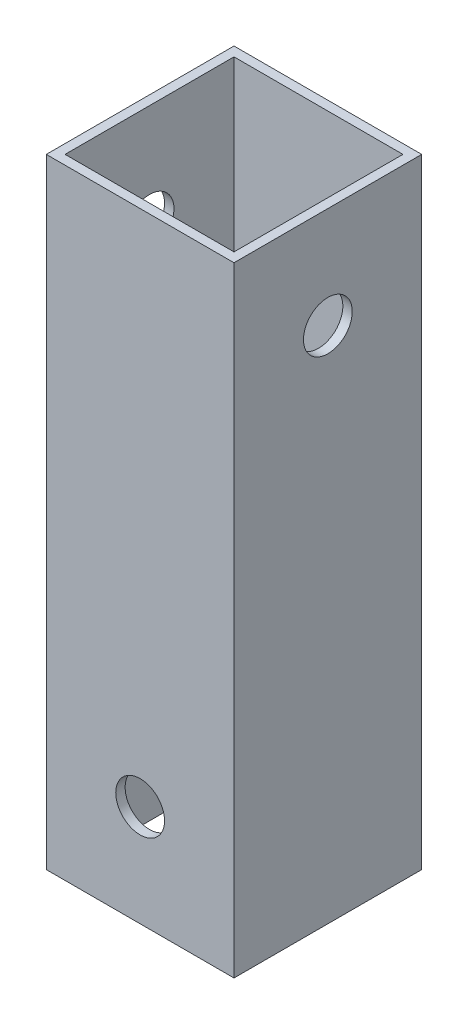
SolidWorks part; units mm, degrees
ref_plane "Front Plane" through (0, 0, 0) normal (0, 0, 1) x (1, 0, 0)
ref_plane "Top Plane" through (0, 0, 0) normal (0, 1, 0) x (1, 0, 0)
ref_plane "Right Plane" through (0, 0, 0) normal (1, 0, 0) x (0, 0, -1)
sketch "Sketch1" plane through (0, 0, 0) normal (0, 1, 0) x (1, 0, 0)
  line L9 (0, 0) -> (20, 0)
  line L10 (0, 0) -> (0, 20)
  line L11 (0, 20) -> (20, 20)
  line L12 (20, 0) -> (20, 20)
  line L13 (1, 1) -> (19, 1)
  line L14 (1, 1) -> (1, 19)
  line L15 (1, 19) -> (19, 19)
  line L16 (19, 1) -> (19, 19)
  dimension "D1" = 20
  dimension "D2" = 20
  dimension "D3" = 18
  dimension "D4" = 1
  dimension "D5" = 1
  dimension "D6" = 18
extrude "Boss-Extrude1" add sketch "Sketch1" along normal blind 66
sketch "Sketch2" plane through (20, 0, 0) normal (1, 0, 0) x (0, 0, -1)
  line L0 (0, 66) -> (20, 66) construction
  line L1 (20, 66) -> (20, 0) construction
  circle A0 centre (10, 55.2) radius 2.6
  dimension "D1" = 5.2
  dimension "D2" = 10.8
  dimension "D3" = 10
extrude "Cut-Extrude1" cut sketch "Sketch2" against normal blind 66
sketch "Sketch3" plane through (0, 0, -20) normal (0, 0, -1) x (-1, 0, 0)
  line L0 (-20, 0) -> (0, 0) construction
  line L1 (0, 66) -> (0, 0) construction
  circle A0 centre (-10, 10.8) radius 2.6
  dimension "D1" = 5.2
  dimension "D2" = 10.8
  dimension "D3" = 10
extrude "Cut-Extrude2" cut sketch "Sketch3" against normal blind 66
